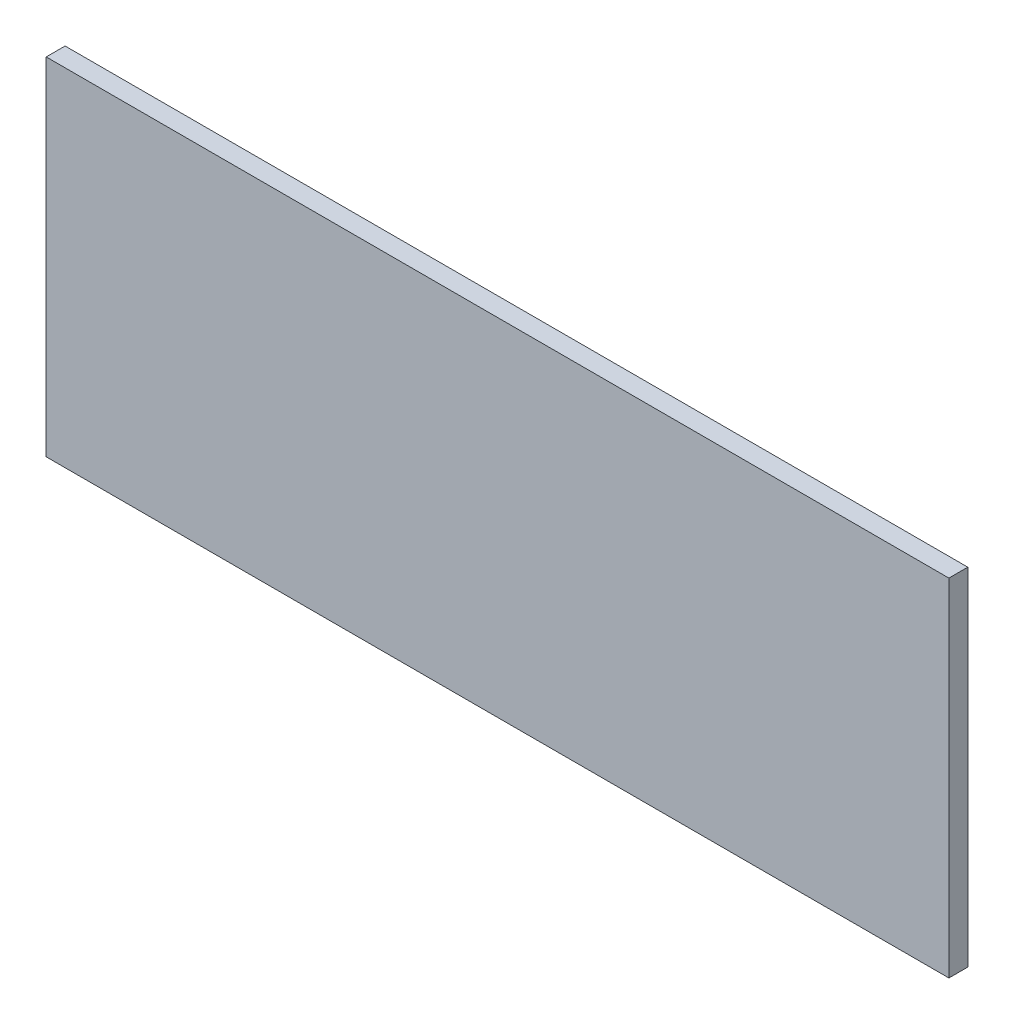
SolidWorks part; units mm, degrees
ref_plane "Front Plane" through (0, 0, 0) normal (0, 0, 1) x (1, 0, 0)
ref_plane "Top Plane" through (0, 0, 0) normal (0, 1, 0) x (1, 0, 0)
ref_plane "Right Plane" through (0, 0, 0) normal (1, 0, 0) x (0, 0, -1)
sketch "Sketch1" plane through (0, 0, 0) normal (0, 0, 1) x (1, 0, 0)
  line L1 (0, 0) -> (219.71, 0)
  line L2 (0, 0) -> (0, 84.3)
  line L3 (0, 84.3) -> (219.71, 84.3)
  line L4 (219.71, 0) -> (219.71, 84.3)
  line L5 (0, 0) -> (219.71, 84.3) construction
  line L6 (0, 84.3) -> (219.71, 0) construction
  point P4 (109.855, 42.15)
  dimension "D1" = 219.71
  dimension "D2" = 84.3
extrude "Boss-Extrude1" add sketch "Sketch1" along normal blind 4.6
equation "\"MDF\"= 4.8mm"
equation "\"Foamcore\"= 4.6mm"
equation "\"GMaterial\"= \"MDF\""
equation "\"PCB\" = 1.6mm"
equation "\"BaseWidth\" = 10in"
equation "\"SkidLength\" = 1in"
equation "\"SkidClearance\" = 0.4in"
equation "\"MotorMountLength\" = 2in"
equation "\"MotorMountWidth\" = \"GMaterial\""
equation "\"MotorMountHeight\" = 2.25in"
equation "\"UnoStackWidth\" = 77.4mm"
equation "\"UnoStackLength\" = 79.8mm"
equation "\"UnoStackHeight\" = 34.2mm"
equation "\"TallHexRiserHeight\" = 22.2mm"
equation "\"PingPongBallSize\" = 40mm"
equation "\"BarrelLength\" = 9in"
equation "\"BarrelSize\" = \"PingPongBallSize\""
equation "\"PlatformLength\" = 4in"
equation "\"PlatformWidth\" = 6in"
equation "\"WheelDiameter\"=2.99213"
equation "\"ServoMountHeight\"=2.49223"
equation "\"ServoGearHeight\" = 0.95330261in"
equation "\"ServoMountLength\"= 1.53774"
equation "\"PivotHoleRadius\"= 0.616358"
equation "\"PlatformMountHeight\" = 3.19"
equation "\"TensionOffSet\"= .3mm"
equation "\"MotorMountWedge\"=0.333333"
equation "\"LaserCutterOffset\"= .3mm"
equation "\"BumperWidth\"=11"
equation "\"PitcherWheelCompression\" = 2.5mm"
equation "\"PitchingWheelWidth\" = 26.2mm"
equation "\"PitchingWheelDiameter\" = 65.5mm"
equation "\"PitchingWheelMountOffset\" = 8.4mm"
equation "\"PitchingWheelInnerDiameter\" = 45.5mm"
equation "\"PitchingWheelBoltShoulder\" = 4.5mm"
equation "\"BrassCouplingLength\" = 18mm"
equation "\"PitchingMotorHeight\" = 57.0mm"
equation "\"PitchingMotorShaftTopHeight\" = \"PitchingMotorHeight\" - 44.1mm"
equation "\"PitchingMotorBodyHeight\" = 38mm"
equation "\"PitchingMotorTopShoulderHeight\" = 40.6mm - \"PitchingMotorBodyHeight\" "
equation "\"PitchingMotorBottomShoulderHeight\" = 40.2mm - \"PitchingMotorBodyHeight\""
equation "\"PitchingMotorBottomShaftHeight\" = \"PitchingMotorHeight\" - \"PitchingMotorShaftTopHeight\" - \"PitchingMotorTopShoulderHeight\" - \"PitchingMotorBodyHeight\" - \"PitchingMotorBottomShoulderHeight\""
equation "\"PitchingMotorShaftDiameter\" = 2.2mm"
equation "\"PitchingMotorBodyDiameter\" = 27.4mm"
equation "\"PitchingMotorTopShoulderDiameter\" = 9.8mm"
equation "\"PitchingMotorBottomShoulderDiameter\" = 9.8mm"
equation "\"BrassCouplingHexSize\" = 12mm"
equation "\"BrassCouplingBoreSize\" = 3.17mm"
equation "\"PitchingMotorMountingHoleDistance\" = 16mm"
equation "\"Acrylic\" = 4.4mm"
equation "\"PitchingMotorDistance\" = \"PitchingWheelDiameter\" + \"PingPongBallSize\" - \"PitcherWheelCompression\"*2"
equation "\"PitchingMotorPlatformOffset\"=1"
equation "\"ServoPlatformOffset\"=1.64173"
equation "\"BallBearingDiameter\" = 22mm"
equation "\"BallBearingWidth\" = 9mm"
equation "\"BallBearingHexShoulder\" = 9mm - 5.9mm"
equation "\"BallBearingHexSize\" = .36in"
equation "\"PlatformMountFootLength\"=0.857143"
equation "\"WheelWidth\"= 26mm"
equation "\"ServoMountReductionBackHeight\"=2.25"
equation "\"PlatformBottomWidthThird\" =  0.857143in"
equation "\"PlatformMountBackReductionHeight\"= 2.5in"
equation "\"PlatformMountBackReductionWidth\"= 3/7in"
equation "\"PlatformMountFrontReductionWidth\" =  1.46226in"
equation "\"PlatformMountFrontReductionHeight\" = 2.5in"
equation "\"HopperLongWallLength\" = 8.646in"
equation "\"HopperShortWallLength\" = 0.9571in"
equation "\"D1@Boss-Extrude1\"=\"Foamcore\""
equation "\"HopperHeight\" = 3.50in - \"Foamcore\""
equation "\"D2@Sketch1\"=\"HopperHeight\""
